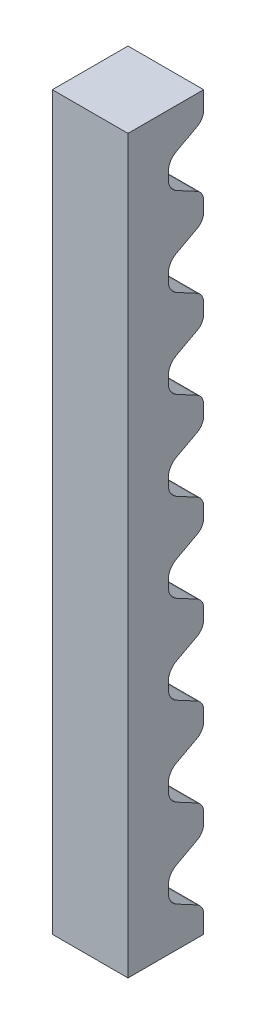
SolidWorks part; units mm, degrees
ref_plane "Front Plane" through (0, 0, 0) normal (0, 0, 1) x (1, 0, 0)
ref_plane "Top Plane" through (0, 0, 0) normal (0, 1, 0) x (1, 0, 0)
ref_plane "Right Plane" through (0, 0, 0) normal (1, 0, 0) x (0, 0, -1)
sketch "Sketch1" plane through (0, 0, 0) normal (1, 0, 0) x (0, 0, -1)
  line L0 (0, 0) -> (0, -290)
  line L1 (0, 0) -> (30, 0)
  line L2 (30, 0) -> (30, -7.0063)
  line L4 (30, -37.9937) -> (30, -42.0063)
  line L5 (19.1667, -29.1964) -> (27.3611, -33.5863)
  line L6 (16, -21.0924) -> (16, -23.9076)
  line L7 (19.1667, -15.8036) -> (27.3611, -11.4137)
  line L9 (16, -56.0924) -> (16, -58.9076)
  line L12 (16, -91.0924) -> (16, -93.9076)
  line L13 (19.1667, -99.1964) -> (27.3611, -103.5863)
  line L14 (19.1667, -120.8036) -> (27.3611, -116.4137)
  line L15 (16, -126.0924) -> (16, -128.9076)
  line L16 (19.1667, -134.1964) -> (27.3611, -138.5863)
  line L17 (19.1667, -155.8036) -> (27.3611, -151.4137)
  line L18 (16, -161.0924) -> (16, -163.9076)
  line L19 (19.1667, -169.1964) -> (27.3611, -173.5863)
  line L20 (19.1667, -190.8036) -> (27.3611, -186.4137)
  line L21 (16, -196.0924) -> (16, -198.9076)
  line L22 (19.1667, -204.1964) -> (27.3611, -208.5863)
  line L23 (19.1667, -225.8036) -> (27.3611, -221.4137)
  line L24 (16, -231.0924) -> (16, -233.9076)
  line L25 (19.1667, -239.1964) -> (27.3611, -243.5863)
  line L26 (19.1667, -260.8036) -> (27.3611, -256.4137)
  line L27 (16, -266.0924) -> (16, -268.9076)
  line L28 (19.1667, -274.1964) -> (27.3611, -278.5863)
  line L29 (30, -72.9937) -> (30, -77.0063)
  line L30 (30, -107.9937) -> (30, -112.0063)
  line L31 (30, -142.9937) -> (30, -147.0063)
  line L32 (30, -177.9937) -> (30, -182.0063)
  line L33 (30, -212.9937) -> (30, -217.0063)
  line L34 (30, -247.9937) -> (30, -252.0063)
  line L36 (30, -282.9937) -> (30, -290)
  line L37 (30, -290) -> (0, -290)
  line L38 (19.1667, -50.8036) -> (27.3611, -46.4137) [skipped]
  line L39 (19.1667, -85.8036) -> (27.3611, -81.4137) [skipped]
  line L40 (27.3611, -46.4137) -> (19.1667, -50.8036)
  line L41 (19.1667, -64.1964) -> (27.3611, -68.5863)
  line L42 (27.3611, -81.4137) -> (19.1667, -85.8036)
  arc A0 (16, -268.9076) -> (19.1667, -274.1964) centre (22, -268.9076) ccw
  arc A1 (19.1667, -260.8036) -> (16, -266.0924) centre (22, -266.0924) ccw
  arc A2 (16, -233.9076) -> (19.1667, -239.1964) centre (22, -233.9076) ccw
  arc A3 (19.1667, -225.8036) -> (16, -231.0924) centre (22, -231.0924) ccw
  arc A4 (16, -198.9076) -> (19.1667, -204.1964) centre (22, -198.9076) ccw
  arc A5 (19.1667, -190.8036) -> (16, -196.0924) centre (22, -196.0924) ccw
  arc A6 (16, -163.9076) -> (19.1667, -169.1964) centre (22, -163.9076) ccw
  arc A7 (19.1667, -155.8036) -> (16, -161.0924) centre (22, -161.0924) ccw
  arc A8 (16, -128.9076) -> (19.1667, -134.1964) centre (22, -128.9076) ccw
  arc A9 (19.1667, -120.8036) -> (16, -126.0924) centre (22, -126.0924) ccw
  arc A10 (16, -93.9076) -> (19.1667, -99.1964) centre (22, -93.9076) ccw
  arc A11 (19.1667, -85.8036) -> (16, -91.0924) centre (22, -91.0924) ccw
  arc A12 (16, -58.9076) -> (19.1667, -64.1964) centre (22, -58.9076) ccw
  arc A13 (19.1667, -50.8036) -> (16, -56.0924) centre (22, -56.0924) ccw
  arc A14 (16, -23.9076) -> (19.1667, -29.1964) centre (22, -23.9076) ccw
  arc A15 (16, -21.0924) -> (19.1667, -15.8036) centre (22, -21.0924) cw
  arc A16 (27.3611, -33.5863) -> (30, -37.9937) centre (25, -37.9937) cw
  arc A17 (30, -7.0063) -> (27.3611, -11.4137) centre (25, -7.0063) cw
  arc A18 (30, -42.0063) -> (27.3611, -46.4137) centre (25, -42.0063) cw
  arc A19 (27.3611, -68.5863) -> (30, -72.9937) centre (25, -72.9937) cw
  arc A20 (30, -77.0063) -> (27.3611, -81.4137) centre (25, -77.0063) cw
  arc A21 (27.3611, -103.5863) -> (30, -107.9937) centre (25, -107.9937) cw
  arc A22 (30, -112.0063) -> (27.3611, -116.4137) centre (25, -112.0063) cw
  arc A23 (27.3611, -138.5863) -> (30, -142.9937) centre (25, -142.9937) cw
  arc A24 (30, -147.0063) -> (27.3611, -151.4137) centre (25, -147.0063) cw
  arc A25 (27.3611, -173.5863) -> (30, -177.9937) centre (25, -177.9937) cw
  arc A26 (30, -182.0063) -> (27.3611, -186.4137) centre (25, -182.0063) cw
  arc A27 (27.3611, -208.5863) -> (30, -212.9937) centre (25, -212.9937) cw
  arc A28 (30, -217.0063) -> (27.3611, -221.4137) centre (25, -217.0063) cw
  arc A29 (27.3611, -243.5863) -> (30, -247.9937) centre (25, -247.9937) cw
  arc A30 (30, -252.0063) -> (27.3611, -256.4137) centre (25, -252.0063) cw
  arc A31 (27.3611, -278.5863) -> (30, -282.9937) centre (25, -282.9937) cw
  point P67 (16, -27.5)
  point P70 (16, -17.5)
  point P73 (30, -35)
  point P76 (30, -10)
  dimension "D7" = 6
  dimension "D2" = 30
  dimension "D9" = 8
  dimension "D11" = 8
extrude "RACK" add sketch "Sketch1" along normal blind 30
ref_plane "Plane1" through (15, 0, 0) normal (1, 0, 0) x (0, 0, -1)
